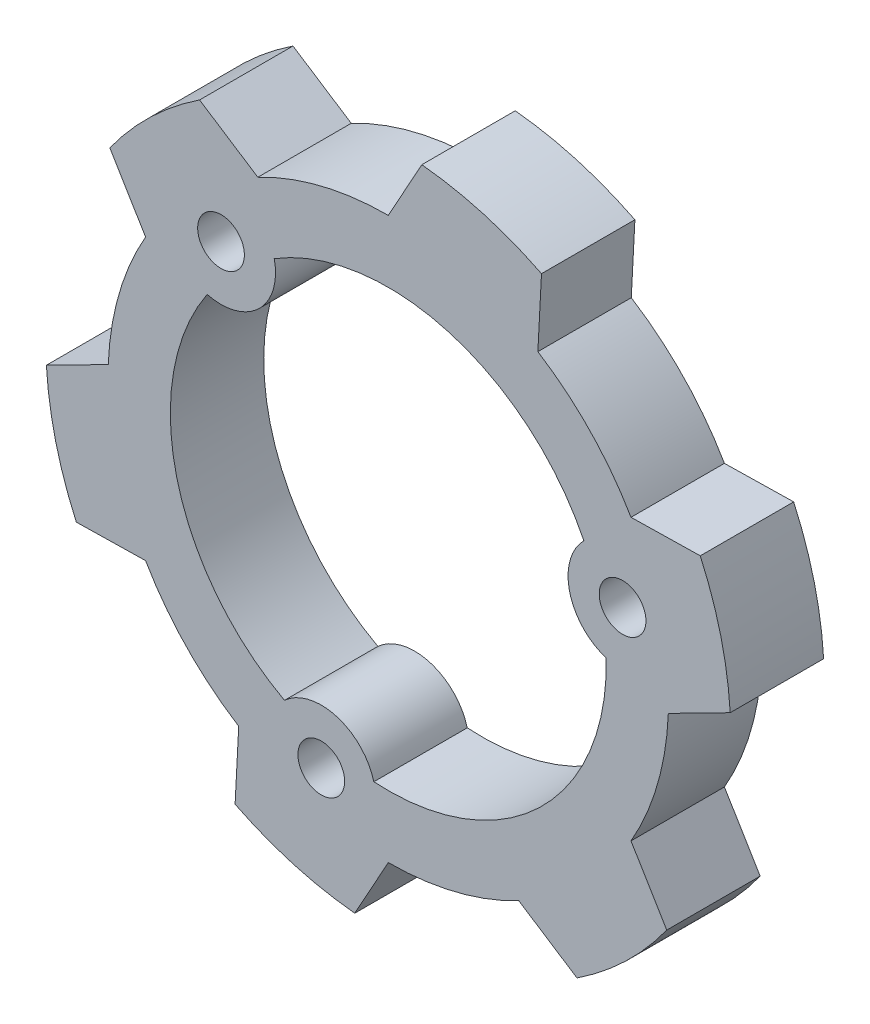
SolidWorks part; units mm, degrees
ref_plane "Plan de face" through (0, 0, 0) normal (0, 0, 1) x (1, 0, 0)
ref_plane "Plan de dessus" through (0, 0, 0) normal (0, 1, 0) x (1, 0, 0)
ref_plane "Plan de droite" through (0, 0, 0) normal (1, 0, 0) x (0, 0, -1)
sketch "Esquisse1" plane through (0, 0, 0) normal (0, 0, 1) x (1, 0, 0)
  line L0 (9.6065, 15.2222) -> (15.5204, 9.1169) construction
  line L3 (0, 18) -> (2.1532, 21.8944)
  line L4 (9.6065, 15.2222) -> (9.8397, 19.6769)
  line L5 (15.5885, 9) -> (20.0377, 9.0824)
  line L6 (17.9861, -0.7083) -> (21.9605, 1.317)
  line L7 (17.9861, -0.7083) -> (15.6556, -8.8826) construction
  line L8 (15.5885, -9) -> (17.8845, -12.8119)
  line L9 (8.3796, -15.9305) -> (12.1208, -18.3599)
  line L10 (8.3796, -15.9305) -> (0.1352, -17.9995) construction
  line L11 (0, -18) -> (-2.1532, -21.8944)
  line L12 (-9.6065, -15.2222) -> (-9.8397, -19.6769)
  line L13 (-9.6065, -15.2222) -> (-15.5204, -9.1169) construction
  line L14 (-15.5885, -9) -> (-20.0377, -9.0824)
  line L15 (-17.9861, 0.7083) -> (-21.9605, -1.317)
  line L16 (-17.9861, 0.7083) -> (-15.6556, 8.8826) construction
  line L17 (-15.5885, 9) -> (-17.8845, 12.8119)
  line L18 (-8.3796, 15.9305) -> (-12.1208, 18.3599)
  line L19 (-8.3796, 15.9305) -> (-0.1352, 17.9995) construction
  line L20 (0, 0) -> (-10.7433, 11.1728) construction
  line L21 (0, 0) -> (-4.3042, -14.8904) construction
  line L22 (0, 0) -> (15.0476, 3.7176) construction
  line L23 (-10.7433, 11.1728) -> (15.0476, 3.7176) construction
  line L24 (15.0476, 3.7176) -> (-4.3042, -14.8904) construction
  line L25 (-4.3042, -14.8904) -> (-10.7433, 11.1728) construction
  arc A0 (0, 18) -> (-8.3796, 15.9305) centre (0, 0) ccw
  arc A1 (9.8397, 19.6769) -> (2.1532, 21.8944) centre (0, 0) ccw
  circle A2 centre (0, 0) radius 22 construction
  arc A3 (21.9605, 1.317) -> (20.0377, 9.0824) centre (0, 0) ccw
  arc A4 (12.1208, -18.3599) -> (17.8845, -12.8119) centre (0, 0) ccw
  arc A5 (-9.8397, -19.6769) -> (-2.1532, -21.8944) centre (0, 0) ccw
  arc A6 (-21.9605, -1.317) -> (-20.0377, -9.0824) centre (0, 0) ccw
  arc A7 (-12.1208, 18.3599) -> (-17.8845, 12.8119) centre (0, 0) ccw
  arc A8 (-15.5885, 9) -> (-17.9861, 0.7083) centre (0, 0) ccw
  arc A9 (-15.5885, -9) -> (-9.6065, -15.2222) centre (0, 0) ccw
  arc A10 (0, -18) -> (8.3796, -15.9305) centre (0, 0) ccw
  arc A11 (15.5885, -9) -> (17.9861, -0.7083) centre (0, 0) ccw
  arc A12 (15.5885, 9) -> (9.6065, 15.2222) centre (0, 0) ccw
  arc A13 (-11.6339, 7.788) -> (-6.6686, -12.3097) centre (0, 0) ccw
  circle A14 centre (-10.7433, 11.1728) radius 1.5
  circle A15 centre (15.0476, 3.7176) radius 1.5
  circle A16 centre (-4.3042, -14.8904) radius 1.5
  arc A17 (-11.6339, 7.788) -> (-7.3262, 11.9301) centre (-10.7433, 11.1728) ccw
  arc A18 (12.5615, 6.1813) -> (13.9949, 0.3797) centre (15.0476, 3.7176) ccw
  arc A19 (-0.9276, -13.9692) -> (-6.6686, -12.3097) centre (-4.3042, -14.8904) ccw
  arc A20 (12.5615, 6.1813) -> (-7.3262, 11.9301) centre (0, 0) ccw
  arc A21 (-0.9276, -13.9692) -> (13.9949, 0.3797) centre (0, 0) ccw
  point P37 (0, 0)
  dimension "D1" = 36
  dimension "D2" = 44
  dimension "D7" = 44
  dimension "D8" = 6
  dimension "D9" = 28
  dimension "D13" = 3
  dimension "D14" = 3
  dimension "D15" = 3
  dimension "D18" = 5.31
  dimension "D19" = 7
  dimension "D20" = 7
  dimension "D21" = 7
  dimension "D3" = 8.5
  dimension "D4" = 10
  dimension "D5" = 8
  dimension "D6" = 4.45
  dimension "D10" = 15.5
  dimension "D11" = 15.5
  dimension "D12" = 15.5
  dimension "D16" = 60
  dimension "D17" = 60
extrude "Boss.-Extru.1" add sketch "Esquisse1" along normal blind 6
